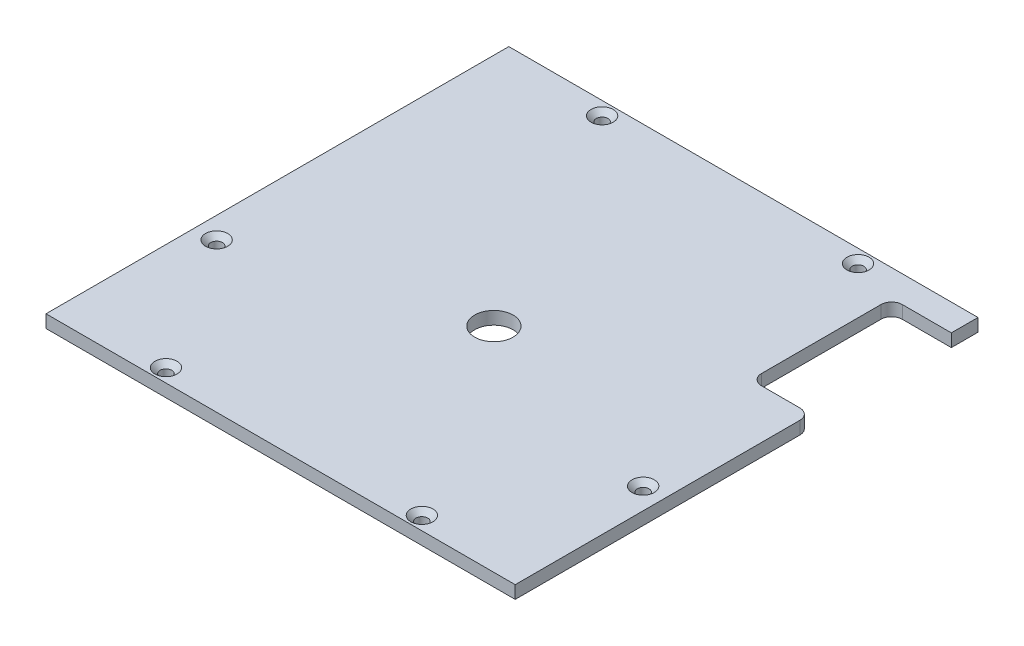
SolidWorks part; units mm, degrees
material "Acrylic (Medium-high impact)"
ref_plane "Front Plane" through (0, 0, 0) normal (0, 0, 1) x (1, 0, 0)
ref_plane "Top Plane" through (0, 0, 0) normal (0, 1, 0) x (1, 0, 0)
ref_plane "Right Plane" through (0, 0, 0) normal (1, 0, 0) x (0, 0, -1)
sketch "Sketch1" plane through (0, 0, 0) normal (0, 1, 0) x (1, 0, 0)
  line L1 (-110, -108.5) -> (110, -108.5)
  line L2 (-110, -108.5) -> (-110, 108.5)
  line L3 (-110, 108.5) -> (110, 108.5)
  line L4 (110, -108.5) -> (110, 108.5)
  line L5 (-110, -108.5) -> (110, 108.5) construction
  line L6 (-110, 108.5) -> (110, -108.5) construction
  point P0 (0, 0)
  dimension "D1" = 220
  dimension "D2" = 217
extrude "Bloco" add sketch "Sketch1" along normal blind 6
sketch "Sketch2" plane through (0, 6, 0) normal (0, 1, 0) x (1, 0, 0)
  line L1 (82, 96) -> (110, 96)
  line L2 (82, 96) -> (82, 30)
  line L3 (82, 30) -> (110, 30)
  line L4 (110, 96) -> (110, 30)
  line L6 (0, -108.5) -> (0, 0) construction
  line L8 (-110, -108.5) -> (110, -108.5) construction
  line L9 (110, 108.5) -> (-110, 108.5) construction
  line L10 (110, -108.5) -> (110, 108.5) construction
  circle A1 centre (0, -8.5) radius 9
  point P14 (0, 0)
  dimension "D4" = 100
  dimension "D5" = 18
  dimension "D1" = 12.5
  dimension "D2" = 66
  dimension "D3" = 28
extrude "Corte Motor" cut sketch "Sketch2" against normal through all
fillet "Raios 5mm" radius 5 3 edges at (110, 3, -30) (82, 3, -30) (82, 3, -96)
sketch "Posição dos Furos" plane through (0, 6, 0) normal (0, 1, 0) x (1, 0, 0)
  line L0 (0, -8.5) -> (0, 108.5) construction
  line L1 (110, 108.5) -> (-110, 108.5) construction
  line L2 (-110, 0) -> (110, 0) construction
  line L3 (-110, 108.5) -> (-110, -108.5) construction
  line L4 (110, -108.5) -> (110, 25) construction
  line L5 (-60, 102.25) -> (60, 102.25) construction
  line L6 (-110, -8.5) -> (110, -8.5) construction
  line L7 (-60, -102.25) -> (60, -102.25) construction
  circle A0 centre (-60, 102.25) radius 2.75
  circle A1 centre (60, 102.25) radius 2.75
  circle A2 centre (-100, -38.5) radius 2.75
  circle A3 centre (60, -102.25) radius 2.75
  circle A4 centre (-60, -102.25) radius 2.75
  circle A5 centre (100, -38.5) radius 2.75
  point P18 (0, -8.5)
  dimension "D1" = 60
  dimension "D2" = 60
  dimension "D3" = 5.5
  dimension "D4" = 6.25
  dimension "D5" = 30
  dimension "D6" = 10
hole_wizard "Furos Escareados - M5 Passante" positions "Sketch4" profile "Sketch5" countersink size "M5" standard "ANSI Metric" end condition through all
sketch "Sketch4" plane through (0, 6, 0) normal (0, 1, 0) x (1, 0, 0)
  point P0 (-100, -38.5)
  point P3 (-60, -102.25)
  point P6 (60, -102.25)
  point P9 (100, -38.5)
  point P12 (-60, 102.25)
  point P15 (60, 102.25)
sketch "Sketch5" plane through (-100, 6, 38.5) normal (1, 0, 0) x (0, 0, 1)
  line L0 (0, 0) -> (0, 6)
  line L1 (0, 6) -> (2.75, 6)
  line L2 (2.75, 6) -> (2.75, 2.45)
  line L3 (2.75, 2.45) -> (5.2, 0)
  line L5 (5.2, 0) -> (0, 0)
  line L6 (-2.75, 2.45) -> (-5.2, 0) construction
  line L11 (0, -6.35) -> (0, 107.95) construction
  dimension "Thru Hole Dia." = 5.5
  dimension "Thru Hole Depth" = 6
  dimension "Near C'Sink Dia." = 10.4
  dimension "Near C'Sink Angle" = 90
